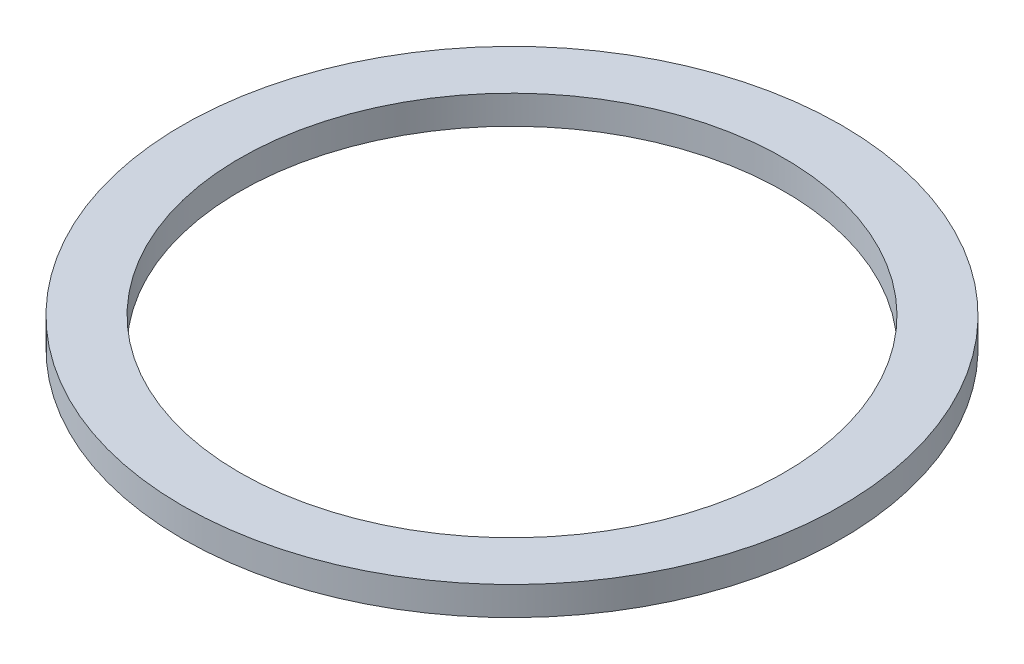
SolidWorks part; units mm, degrees
ref_plane "Front Plane" through (0, 0, 0) normal (0, 0, 1) x (1, 0, 0)
ref_plane "Top Plane" through (0, 0, 0) normal (0, 1, 0) x (1, 0, 0)
ref_plane "Right Plane" through (0, 0, 0) normal (1, 0, 0) x (0, 0, -1)
sketch "Sketch1" plane through (0, 0, 0) normal (0, 1, 0) x (1, 0, 0)
  circle A0 centre (0, 0) radius 47.5
  circle A1 centre (0, 0) radius 57.5
  dimension "D1" = 95
  dimension "D2" = 115
extrude "Boss-Extrude1" add sketch "Sketch1" along normal mid plane 5
